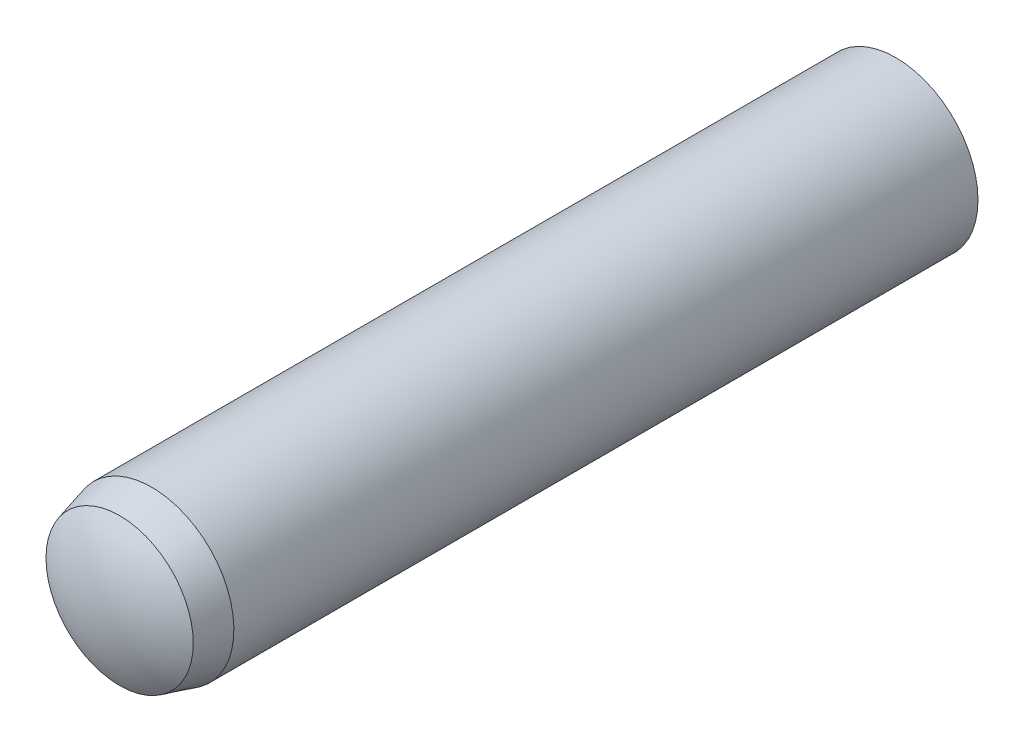
SolidWorks part; units mm, degrees
ref_plane "Front Plane" through (0, 0, 0) normal (0, 0, 1) x (1, 0, 0)
ref_plane "Top Plane" through (0, 0, 0) normal (0, 1, 0) x (1, 0, 0)
ref_plane "Right Plane" through (0, 0, 0) normal (1, 0, 0) x (0, 0, -1)
sketch "Sketch1" plane through (0, 0, 0) normal (0, 0, 1) x (1, 0, 0)
  circle A0 centre (0, 0) radius 5
  point P3 (0, 5)
  dimension "Diameter" = 10
sketch "Sketch2" plane through (0, 0, 0) normal (1, 0, 0) x (0, 0, -1)
  line L0 (-25, 0) -> (25, 0) construction
  line L1 (-25, 0) -> (-25, 5) construction
  line L2 (-25, 5) -> (25, 5)
  line L3 (25, 5) -> (25, 0) construction
  line L4 (-23.7, 4.4775) -> (-21.75, 5)
  arc A0 (-25, 0) -> (-23.7, 4.4775) centre (-16.6392, 0) cw
  arc A1 (25, 0) -> (23.5, 5) centre (15.9167, 0) ccw
  point P2 (0, 0)
  point P11 (-15, 0)
  point P13 (15, 0)
  dimension "Length" = 50
  dimension "D1" = 15
  dimension "D2" = 1.5
  dimension "D3" = 3.25
  dimension "D4" = 1.95
  dimension "D5" = 10
  dimension "D6" = 10
sketch "Sketch3" plane through (0, 0, 0) normal (1, 0, 0) x (0, 0, -1)
  line L0 (-25, 0) -> (25, 0) construction
  line L1 (-23.7, 4.4775) -> (-21.75, 5) construction
  line L2 (-25, 0) -> (25, 0)
  line L3 (-23.7, 4.4775) -> (-21.75, 5)
  line L4 (-21.75, 5) -> (23.5, 5)
  arc A0 (25, 0) -> (23.5, 5) centre (15.9167, 0) ccw construction
  arc A1 (-23.7, 4.4775) -> (-25, 0) centre (-16.6392, 0) ccw construction
  arc A2 (25, 0) -> (23.5, 5) centre (15.9167, 0) ccw
  arc A3 (-23.7, 4.4775) -> (-25, 0) centre (-16.6392, 0) ccw
revolve "Revolve1" add sketch "Sketch3" angle 360 about L2
equation "\"D2@Sketch2\" = \"Diameter@Sketch1\" * .15"
equation "\"D3@Sketch2\" = \"Diameter@Sketch1\" * .325"
equation "\"D4@Sketch2\" = \"D3@Sketch2\" * .6"
equation "\"D5@Sketch2\"=\"Diameter@Sketch1\""
equation "\"D6@Sketch2\"=\"D5@sketch2\""
